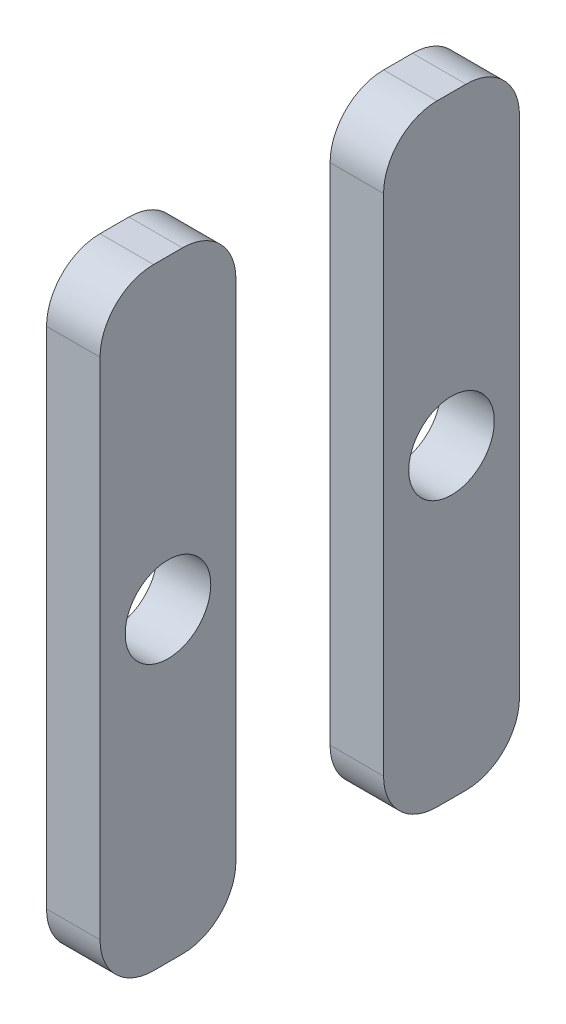
SolidWorks part; units mm, degrees
material "ASTM A36 Acero"
ref_plane "Alzado" through (0, 0, 0) normal (0, 0, 1) x (1, 0, 0)
ref_plane "Planta" through (0, 0, 0) normal (0, 1, 0) x (1, 0, 0)
ref_plane "Vista lateral" through (0, 0, 0) normal (1, 0, 0) x (0, 0, -1)
sketch "Croquis1" plane through (0, 0, 0) normal (1, 0, 0) x (0, 0, -1)
  line L0 (-26.5, 0) -> (26.5, 0) construction
  line L1 (0, 0) -> (0, -13.1504) construction
  line L2 (-39.2, 57.155) -> (-13.8, 57.155)
  line L3 (-39.2, 57.155) -> (-39.2, -57.155)
  line L4 (-39.2, -57.155) -> (-13.8, -57.155)
  line L5 (-13.8, 57.155) -> (-13.8, -57.155)
  line L6 (-39.2, 57.155) -> (-13.8, -57.155) construction
  line L7 (-39.2, -57.155) -> (-13.8, 57.155) construction
  line L8 (39.2, -57.155) -> (13.8, -57.155)
  line L9 (13.8, 57.155) -> (13.8, -57.155)
  line L10 (39.2, 57.155) -> (13.8, 57.155)
  line L11 (39.2, 57.155) -> (39.2, -57.155)
  circle A0 centre (-26.5, 0) radius 8
  circle A1 centre (26.5, 0) radius 8
  point P4 (0, 0)
  dimension "D4" = 16
  dimension "D1" = 53
  dimension "D2" = 114.31
  dimension "D3" = 25.4
extrude "Saliente-Extruir2" add sketch "Croquis1" along normal blind 10
fillet "Redondeo1" radius 10 4 edges at (5, -57.155, 13.8) (5, -57.155, 39.2) (5, 57.155, 13.8) (5, 57.155, 39.2)
fillet "Redondeo2" radius 10 4 edges at (5, -57.155, -13.8) (5, -57.155, -39.2) (5, 57.155, -13.8) (5, 57.155, -39.2)
